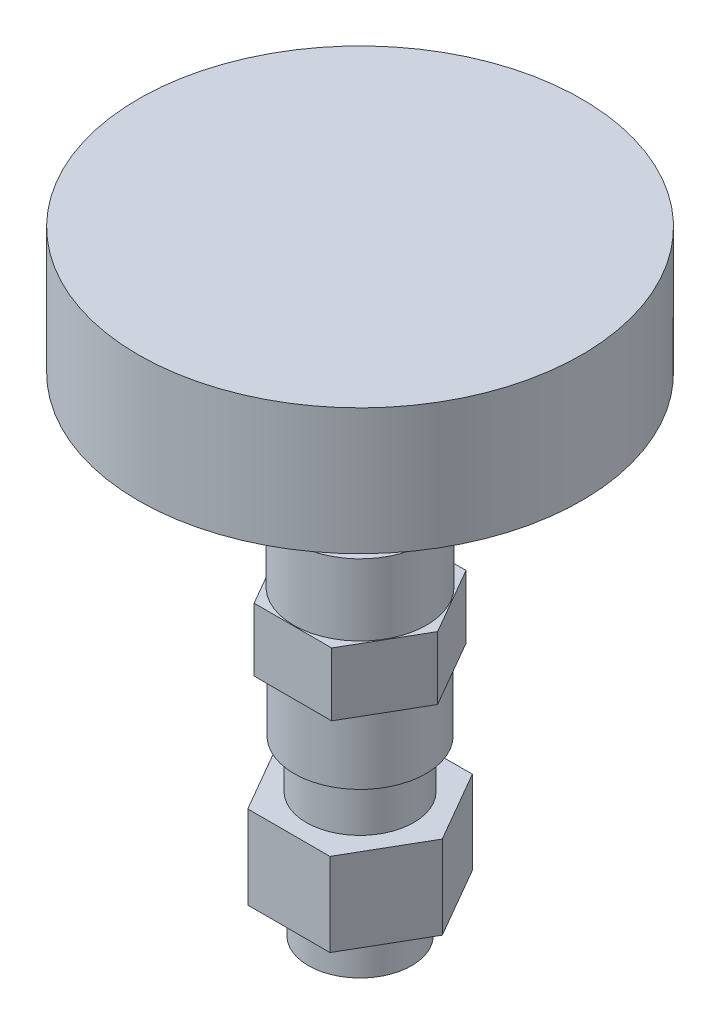
SolidWorks part; units mm, degrees
ref_plane "Front Plane" through (0, 0, 0) normal (0, 0, 1) x (1, 0, 0)
ref_plane "Top Plane" through (0, 0, 0) normal (0, 1, 0) x (1, 0, 0)
ref_plane "Right Plane" through (0, 0, 0) normal (1, 0, 0) x (0, 0, -1)
sketch "Sketch1" plane through (0, 0, 0) normal (0, 1, 0) x (1, 0, 0)
  circle A0 centre (0, 0) radius 4.8895
extrude "Boss-Extrude1" add sketch "Sketch1" along normal blind 3.937
sketch "Sketch2" plane through (0, 3.937, 0) normal (0, 1, 0) x (1, 0, 0)
  line L1 (7.7723, 0) -> (3.8861, 6.731)
  line L2 (3.8861, 6.731) -> (-3.8861, 6.731)
  line L3 (-3.8861, 6.731) -> (-7.7723, 0)
  line L4 (-7.7723, 0) -> (-3.8861, -6.731)
  line L5 (-3.8861, -6.731) -> (3.8861, -6.731)
  line L6 (3.8861, -6.731) -> (7.7723, 0)
  circle A0 centre (0, 0) radius 6.731 construction
extrude "Boss-Extrude2" add sketch "Sketch2" along normal blind 7.874
sketch "Sketch3" plane through (0, 11.811, 0) normal (0, 1, 0) x (1, 0, 0)
  circle A0 centre (0, 0) radius 5.08
extrude "Boss-Extrude3" add sketch "Sketch3" along normal blind 4.572
sketch "Sketch4" plane through (0, 16.383, 0) normal (0, 1, 0) x (1, 0, 0)
  circle A0 centre (0, 0) radius 6.223
extrude "Boss-Extrude4" add sketch "Sketch4" along normal blind 6.223
sketch "Sketch5" plane through (0, 22.606, 0) normal (0, 1, 0) x (1, 0, 0)
  line L1 (7.3323, 0) -> (3.6662, 6.35)
  line L2 (3.6662, 6.35) -> (-3.6662, 6.35)
  line L3 (-3.6662, 6.35) -> (-7.3323, 0)
  line L4 (-7.3323, 0) -> (-3.6662, -6.35)
  line L5 (-3.6662, -6.35) -> (3.6662, -6.35)
  line L6 (3.6662, -6.35) -> (7.3323, 0)
  circle A0 centre (0, 0) radius 6.35 construction
extrude "Boss-Extrude5" add sketch "Sketch5" along normal blind 5.969
sketch "Sketch6" plane through (0, 28.575, 0) normal (0, 1, 0) x (1, 0, 0)
  circle A0 centre (0, 0) radius 6.2865
extrude "Boss-Extrude6" add sketch "Sketch6" along normal blind 6.731
sketch "Sketch7" plane through (0, 35.306, 0) normal (0, 1, 0) x (1, 0, 0)
  circle A0 centre (0, 0) radius 5.2705
extrude "Boss-Extrude7" add sketch "Sketch7" along normal blind 4.318
sketch "Sketch9" plane through (0, 39.624, 0) normal (0, 1, 0) x (1, 0, 0)
  line L1 (-5.461, -5.461) -> (5.461, -5.461)
  line L2 (-5.461, -5.461) -> (-5.461, 5.461)
  line L3 (-5.461, 5.461) -> (5.461, 5.461)
  line L4 (5.461, -5.461) -> (5.461, 5.461)
  line L5 (-5.461, -5.461) -> (5.461, 5.461) construction
  line L6 (-5.461, 5.461) -> (5.461, -5.461) construction
  point P0 (0, 0)
  dimension "D1" = 10.922
  dimension "D2" = 10.922
extrude "Boss-Extrude8" add sketch "Sketch9" along normal blind 6.477
sketch "Sketch10" plane through (0, 46.101, 0) normal (0, 1, 0) x (1, 0, 0)
  circle A0 centre (0, 0) radius 20.955
  dimension "D1" = 41.91
extrude "Boss-Extrude9" add sketch "Sketch10" along normal blind 11.938
sketch "Sketch11" plane through (0, 0, 0) normal (0, -1, 0) x (1, 0, 0)
  circle A0 centre (0, 0) radius 3.1813
extrude "Cut-Extrude1" cut sketch "Sketch11" against normal blind 11.938
